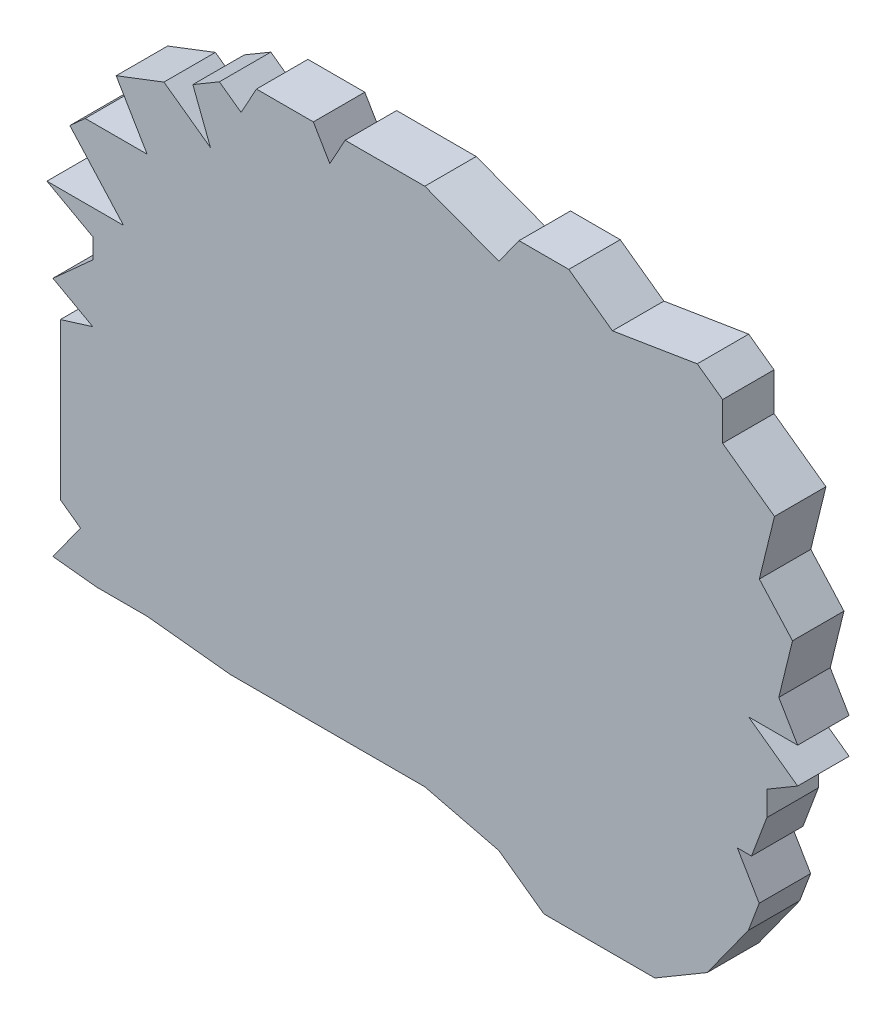
SolidWorks part; units mm, degrees
ref_plane "Спереди" through (0, 0, 0) normal (0, 0, 1) x (1, 0, 0)
ref_plane "Сверху" through (0, 0, 0) normal (0, 1, 0) x (1, 0, 0)
ref_plane "Справа" through (0, 0, 0) normal (1, 0, 0) x (0, 0, -1)
sketch "Эскиз1" plane through (0, 0, 0) normal (0, 0, 1) x (1, 0, 0)
  line L0 (210.0522, 1043.9175) -> (1362.0522, 1043.9175) construction
  line L5 (-76.7634, 65.7416) -> (73.2366, -84.2584) construction
  line L6 (-76.7634, -84.2584) -> (73.2366, 65.7416) construction
  line L7 (-66.2826, 4.0904) -> (-74.0405, 8.3573)
  line L8 (-74.0405, 8.3573) -> (-70.1615, 11.8483)
  line L9 (-70.1615, 11.8483) -> (-66.2826, 15.3394)
  line L10 (-66.2826, 15.3394) -> (-66.2826, 19.2183)
  line L11 (-66.2826, 19.2183) -> (-75.2094, 24.128)
  line L12 (-75.2094, 24.128) -> (-60.3142, 24.128)
  line L13 (-60.3142, 24.128) -> (-70.746, 35.7189)
  line L14 (-70.746, 35.7189) -> (-67.7618, 38.4046)
  line L15 (-67.7618, 38.4046) -> (-55.7301, 38.4046)
  line L16 (-55.7301, 38.4046) -> (-61.746, 48.607)
  line L17 (-61.746, 48.607) -> (-52.461, 52.1753)
  line L18 (-52.461, 52.1753) -> (-43.4163, 45.6655)
  line L19 (-43.4163, 45.6655) -> (-46.8387, 54.5707)
  line L20 (-46.8387, 54.5707) -> (-41.6844, 57.61)
  line L21 (-41.6844, 57.61) -> (-37.4616, 54.5707)
  line L22 (-37.4616, 54.5707) -> (-34.4773, 59.9968)
  line L23 (-34.4773, 59.9968) -> (-23.4203, 59.9968)
  line L24 (-23.4203, 59.9968) -> (-20.2208, 54.5707)
  line L25 (-20.2208, 54.5707) -> (-17.2365, 59.9968)
  line L26 (-17.2365, 59.9968) -> (-1.7634, 59.9968)
  line L27 (-1.7634, 59.9968) -> (12.6539, 54.5707)
  line L28 (12.6539, 54.5707) -> (16.5592, 59.9968)
  line L29 (16.5592, 59.9968) -> (26.2302, 59.9968)
  line L30 (26.2302, 59.9968) -> (34.7104, 53.8932)
  line L31 (34.7104, 53.8932) -> (51.1976, 56.58)
  line L32 (51.1976, 56.58) -> (56.1242, 53.0341)
  line L33 (56.1242, 53.0341) -> (56.1242, 45.6655)
  line L34 (56.1242, 45.6655) -> (66.2124, 38.4046)
  line L35 (66.2124, 38.4046) -> (63.2645, 26.3811)
  line L36 (63.2645, 26.3811) -> (69.711, 19.2183)
  line L37 (69.711, 19.2183) -> (67.0481, 8.3573)
  line L38 (67.0481, 8.3573) -> (70.7129, 2.1422)
  line L39 (70.7129, 2.1422) -> (61.1683, 2.1422)
  line L40 (61.1683, 2.1422) -> (70.7129, -4.7274)
  line L41 (70.7129, -4.7274) -> (64.7385, -8.2502)
  line L42 (64.7385, -8.2502) -> (64.7385, -13.0281)
  line L43 (64.7385, -13.0281) -> (61.7357, -21.0067)
  line L44 (61.7357, -21.0067) -> (58.996, -21.0067)
  line L45 (58.996, -21.0067) -> (63.2371, -28.1993)
  line L46 (63.2371, -28.1993) -> (61.1165, -33.8337)
  line L47 (61.1165, -33.8337) -> (53.1384, -44.9184)
  line L48 (53.1384, -44.9184) -> (42.954, -50.9237)
  line L49 (42.954, -50.9237) -> (34.7104, -50.9237)
  line L50 (34.7104, -50.9237) -> (21.3947, -50.9237)
  line L51 (21.3947, -50.9237) -> (12.6539, -44.6325)
  line L52 (12.6539, -44.6325) -> (-1.7634, -41.0978)
  line L53 (-1.7634, -41.0978) -> (-17.2365, -41.0978)
  line L54 (-17.2365, -41.0978) -> (-39.573, -41.0978)
  line L55 (-39.573, -41.0978) -> (-55.7301, -39.376)
  line L56 (-55.7301, -39.376) -> (-65.5301, -39.376)
  line L57 (-65.5301, -39.376) -> (-74.0405, -38.4692)
  line L58 (-74.0405, -38.4692) -> (-68.6764, -31.0165)
  line L59 (-68.6764, -31.0165) -> (-72.5906, -28.1993)
  line L60 (-72.5906, -28.1993) -> (-72.5906, -19.7651)
  line L61 (-72.5906, -19.7651) -> (-72.5906, -11.8132)
  line L62 (-72.5906, -11.8132) -> (-72.5906, -8.2502)
  line L63 (-72.5906, -8.2502) -> (-72.5906, 2.1422)
  line L64 (-72.5906, 2.1422) -> (-66.2826, 4.0904)
  point P0 (-1.7634, -9.2584)
extrude "Бобышка-Вытянуть1" add sketch "Эскиз1" along normal blind 10 contours L64 L7 L8 L9 L10 L11 L12 L13 L14 L15 L16 L17 L18 L19 L20 L21 L22 L23 L24 L25 L26 L27 L28 L29 L30 L31 L32 L33 L34 L35 L36 L37 L38 L39 L40 L41 L42 L43 L44 L45 L46 L47 L48 L49 L50 L51 L52 L53 L54 L55 L56 L57 L58 L59 L60 L61 L62 L63
